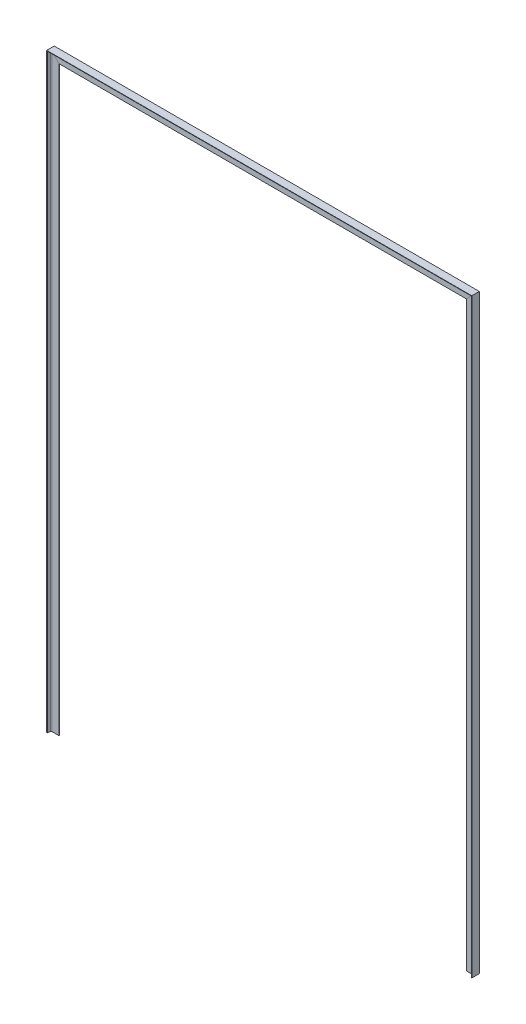
SolidWorks part; units mm, degrees
material "ASTM A36 Steel"
ref_plane "Front Plane" through (0, 0, 0) normal (0, 0, 1) x (1, 0, 0)
ref_plane "Top Plane" through (0, 0, 0) normal (0, 1, 0) x (1, 0, 0)
ref_plane "Right Plane" through (0, 0, 0) normal (1, 0, 0) x (0, 0, -1)
sketch "Sketch1" plane through (0, 0, 0) normal (0, 0, 1) x (1, 0, 0)
  line L0 (0, 0) -> (0, 10000)
  line L1 (0, 10000) -> (7000, 10000)
  line L2 (7000, 10000) -> (7000, 0)
  dimension "D1" = 10000
  dimension "D2" = 7000
other "St section ST6X17.5(1)"
ref_plane "Plane1" through (0, 0, 0) normal (0, 1, 0) x (0, 0, -1)
sketch "Sketch11" plane through (0, 0, 0) normal (0, 1, 0) x (0, 0, -1)
  line L0 (-64.4906, 152.4) -> (64.4906, 152.4)
  line L2 (-5.4356, 0) -> (-5.4356, 123.952)
  line L3 (-14.9864, 135.2265) -> (-60.0336, 142.7349)
  line L5 (-64.4906, 152.4) -> (-64.4906, 147.9963)
  line L6 (64.4906, 152.4) -> (64.4906, 147.9963)
  line L7 (60.0336, 142.7349) -> (14.9864, 135.2265)
  line L8 (5.4356, 123.952) -> (5.4356, 0)
  line L9 (64.4906, 138.557) -> (-64.4906, 138.557) construction
  line L12 (-5.4356, 0) -> (5.4356, 0)
  arc A0 (-60.0336, 142.7349) -> (-64.4906, 147.9963) centre (-59.1566, 147.9963) cw
  arc A1 (-5.4356, 123.952) -> (-14.9864, 135.2265) centre (-16.8656, 123.952) ccw
  arc A2 (14.9864, 135.2265) -> (5.4356, 123.952) centre (16.8656, 123.952) ccw
  arc A3 (60.0336, 142.7349) -> (64.4906, 147.9963) centre (59.1566, 147.9963) ccw
  point P9 (0, 152.4)
  point P18 (0, 33.9014)
  point P20 (-5.4356, 61.976)
  point P22 (5.4356, 61.976)
  point P23 (0, 0)
  point P24 (0, 0)
  dimension "RI" = 11.43
  dimension "D2" = 9.463
  dimension "RA" = 5.334
  dimension "D1" = 123.952
  dimension "TW" = 10.8712
  dimension "BF" = 128.9812
  dimension "DEPTH" = 152.4
  dimension "TF" = 13.843
  dimension "delta" = 59.055
